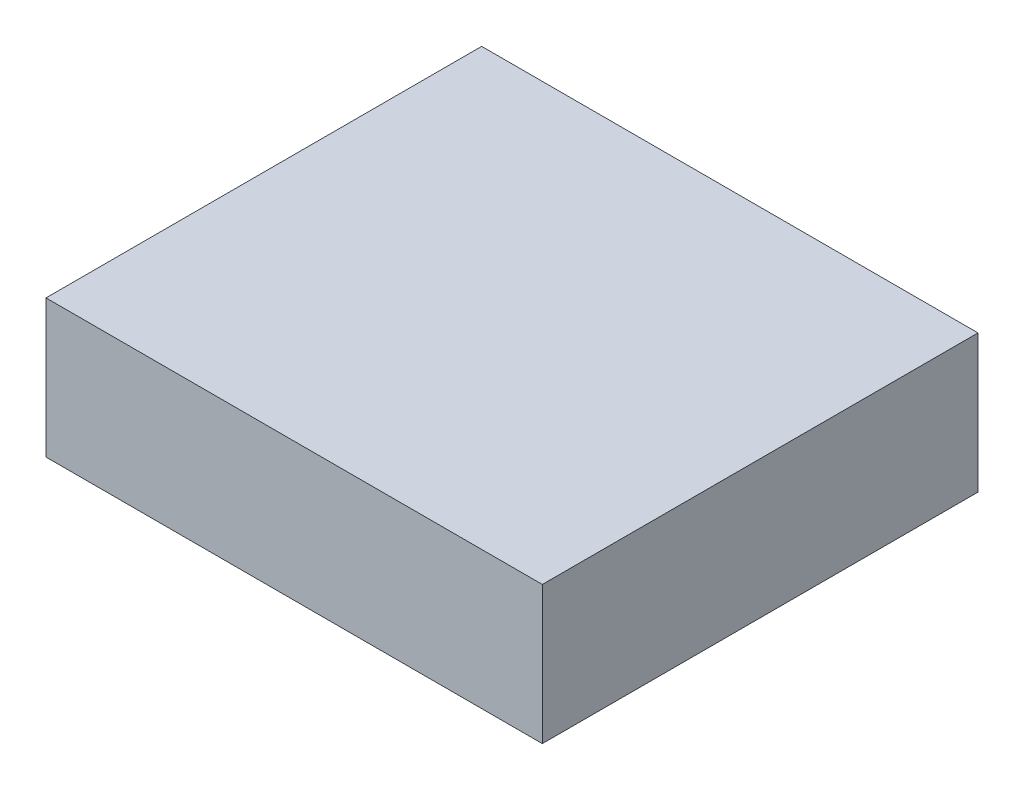
SolidWorks part; units mm, degrees
ref_plane "Front Plane" through (0, 0, 0) normal (0, 0, 1) x (1, 0, 0)
ref_plane "Top Plane" through (0, 0, 0) normal (0, 1, 0) x (1, 0, 0)
ref_plane "Right Plane" through (0, 0, 0) normal (1, 0, 0) x (0, 0, -1)
sketch "Sketch1" plane through (0, 0, 0) normal (0, 1, 0) x (1, 0, 0)
  line L1 (-45, -39.5) -> (45, -39.5)
  line L2 (-45, -39.5) -> (-45, 39.5)
  line L3 (-45, 39.5) -> (45, 39.5)
  line L4 (45, -39.5) -> (45, 39.5)
  line L5 (-45, -39.5) -> (45, 39.5) construction
  line L6 (-45, 39.5) -> (45, -39.5) construction
  point P0 (0, 0)
  dimension "D1" = 90
  dimension "D2" = 79
extrude "Boss-Extrude1" add sketch "Sketch1" along normal blind 25
sketch "Sketch2" plane through (-45, 0, 0) normal (-1, 0, 0) x (0, 0, 1)
  line L1 (-31.3291, 19.1379) -> (-16.1085, 19.1379)
  line L2 (-31.3291, 19.1379) -> (-31.3291, 7.6379)
  line L3 (-31.3291, 7.6379) -> (-16.1085, 7.6379)
  line L4 (-16.1085, 19.1379) -> (-16.1085, 7.6379)
extrude "Boss-Extrude2" add sketch "Sketch2" along normal blind 4.5
